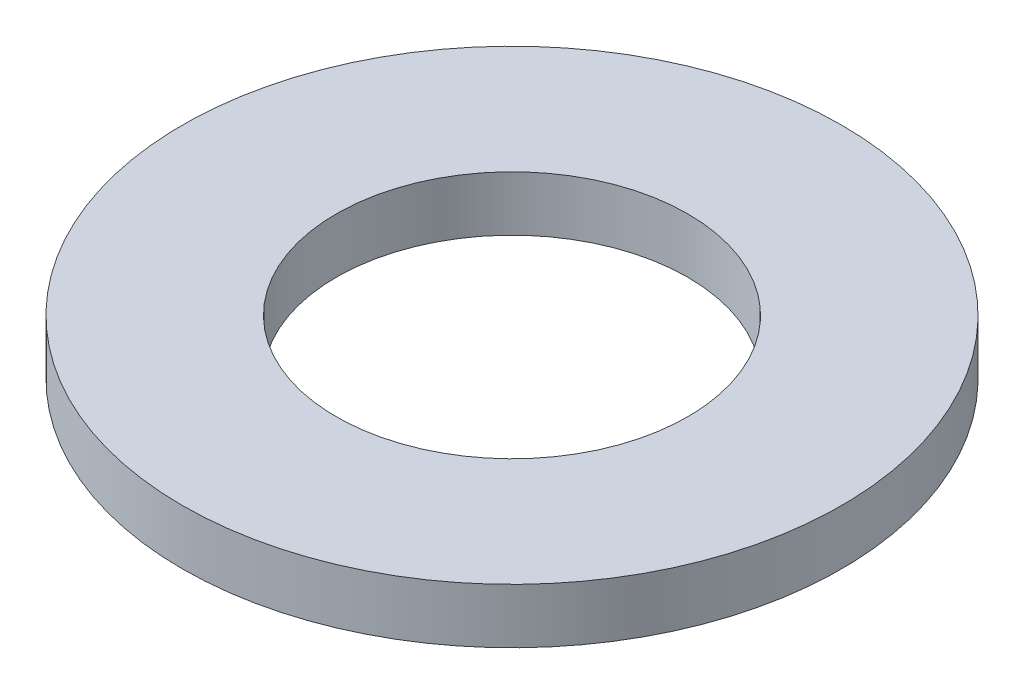
SolidWorks part; units mm, degrees
material "Cast Stainless Steel"
ref_plane "Front Plane" through (0, 0, 0) normal (0, 0, 1) x (1, 0, 0)
ref_plane "Top Plane" through (0, 0, 0) normal (0, 1, 0) x (1, 0, 0)
ref_plane "Right Plane" through (0, 0, 0) normal (1, 0, 0) x (0, 0, -1)
sketch "Sketch1" plane through (0, 0, 0) normal (0, 1, 0) x (1, 0, 0)
  circle A0 centre (0, 0) radius 6
  circle A1 centre (0, 0) radius 3.2
  dimension "D1" = 12
  dimension "D2" = 6.4
extrude "Boss-Extrude1" add sketch "Sketch1" along normal blind 1
move or copy body "Body-Move/Copy1" bodies to move or copy 101
